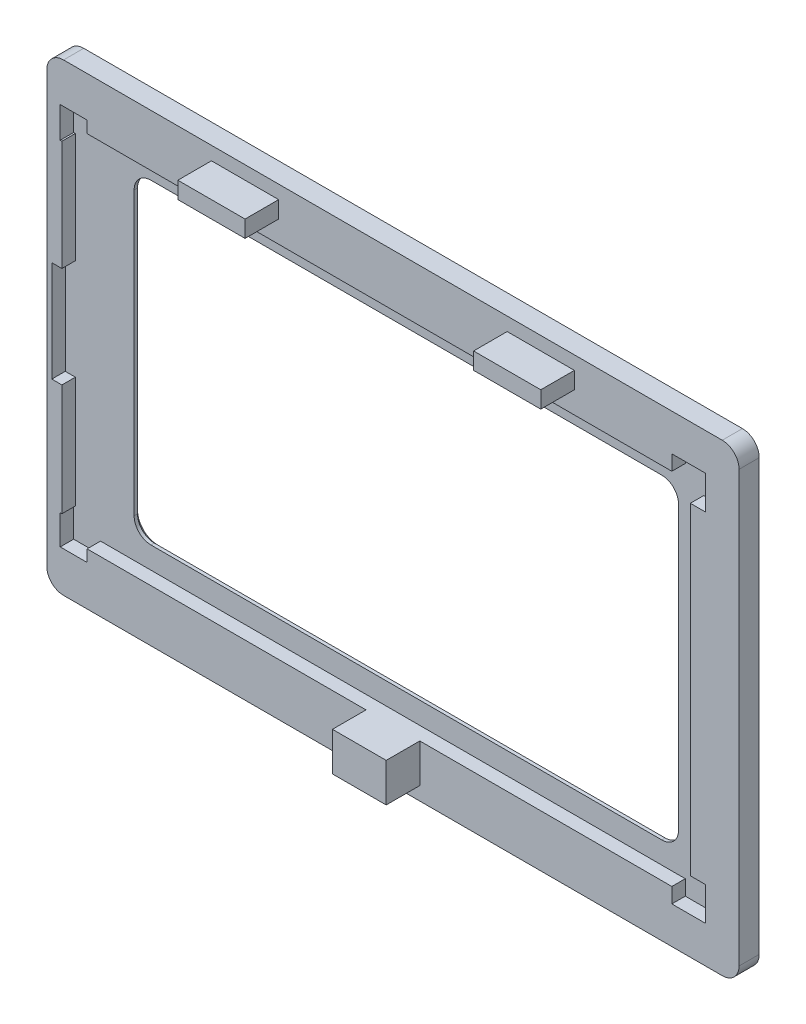
SolidWorks part; units mm, degrees
ref_plane "Front Plane" through (0, 0, 0) normal (0, 0, 1) x (1, 0, 0)
ref_plane "Top Plane" through (0, 0, 0) normal (0, 1, 0) x (1, 0, 0)
ref_plane "Right Plane" through (0, 0, 0) normal (1, 0, 0) x (0, 0, -1)
sketch "Sketch1" plane through (0, 0, 0) normal (0, 0, 1) x (1, 0, 0)
  line L1 (113.8284, 62.9439) -> (10.8284, 62.9439)
  line L2 (113.8284, 62.9439) -> (113.8284, -6.0561)
  line L3 (113.8284, -6.0561) -> (10.8284, -6.0561)
  line L4 (10.8284, 62.9439) -> (10.8284, -6.0561)
  dimension "D1" = 69
  dimension "D2" = 103
extrude "Boss-Extrude1" add sketch "Sketch1" along normal blind 3
sketch "Sketch2" plane through (0, 0, 3) normal (0, 0, 1) x (1, 0, 0)
  line L0 (10.8284, 62.9439) -> (10.8284, -6.0561) construction
  line L1 (21.8284, 51.9439) -> (102.8284, 51.9439)
  line L2 (21.8284, 51.9439) -> (21.8284, 4.9439)
  line L3 (21.8284, 4.9439) -> (102.8284, 4.9439)
  line L4 (102.8284, 51.9439) -> (102.8284, 4.9439)
  line L5 (113.8284, 62.9439) -> (10.8284, 62.9439) construction
  line L6 (113.8284, -6.0561) -> (113.8284, 62.9439) construction
  line L7 (10.8284, -6.0561) -> (113.8284, -6.0561) construction
  dimension "D1" = 11
  dimension "D2" = 11
  dimension "D3" = 11
  dimension "D4" = 11
extrude "Cut-Extrude1" cut sketch "Sketch2" against normal blind 3
sketch "Sketch3" plane through (0, 0, 3) normal (0, 0, 1) x (1, 0, 0)
  line L0 (113.8284, -6.0561) -> (113.8284, 62.9439) construction
  line L1 (13.0784, 55.1939) -> (106.5784, 55.1939)
  line L2 (13.0784, 55.1939) -> (13.0784, 35.9439)
  line L3 (13.0784, 1.6939) -> (106.5784, 1.6939)
  line L11 (106.5784, 55.1939) -> (106.5784, 1.6939)
  line L12 (13.0784, 20.9439) -> (13.0784, 1.6939)
  line L13 (13.0784, 35.9439) -> (11.5784, 35.9439)
  line L15 (13.0784, 20.9439) -> (11.5784, 20.9439)
  line L16 (11.5784, 35.9439) -> (11.5784, 20.9439)
  line L18 (21.8284, 51.9439) -> (21.8284, 4.9439) construction
  point P13 (113.8284, 28.4439)
  point P14 (106.5784, 28.4439)
  dimension "D1" = 93.5
  dimension "D2" = 53.5
  dimension "D3" = 8.75
  dimension "D4" = 1.5
  dimension "D5" = 15
  dimension "D6" = 19.25
extrude "Cut-Extrude2" cut sketch "Sketch3" against normal blind 2
fillet "Fillet2" radius 2.5 4 edges at (113.8284, 62.9439, 1.5) (10.8284, 62.9439, 1.5) (10.8284, -6.0561, 1.5) (113.8284, -6.0561, 1.5)
fillet "Fillet3" radius 2.5 4 edges at (21.8284, 51.9439, 0.5) (21.8284, 4.9439, 0.5) (102.8284, 4.9439, 0.5) (102.8284, 51.9439, 0.5)
chamfer "Chamfer1" distance 0.5 angle 45 8 edges at (62.3284, 4.9439, 0) (102.8284, 28.4439, 0) (62.3284, 51.9439, 0) (21.8284, 28.4439, 0) (102.0961, 51.2116, 0) (102.0961, 5.6761, 0) (22.5606, 51.2116, 0) (22.5606, 5.6761, 0)
sketch "Sketch4" plane through (0, 0, 3) normal (0, 0, 1) x (1, 0, 0)
  line L0 (14.3284, 52.8439) -> (12.8284, 52.8439) construction
  line L1 (16.8284, 55.1939) -> (16.8284, 56.9439)
  line L2 (106.5784, 55.1939) -> (13.0784, 55.1939) construction
  line L4 (16.8284, 55.1939) -> (13.0784, 55.1939)
  line L5 (13.0784, 55.1939) -> (13.0784, 52.3439)
  line L7 (13.0784, 55.1939) -> (13.0784, 35.9439) construction
  line L8 (13.0784, 52.3439) -> (12.8284, 52.3439)
  line L9 (16.8284, 56.9439) -> (12.8284, 56.9439)
  line L10 (12.8284, 56.4439) -> (12.8284, 60.9439) construction
  line L11 (12.8284, 56.9439) -> (12.8284, 52.3439)
  line L12 (16.3284, 56.4439) -> (12.8284, 56.4439) construction
  line L13 (16.3284, 52.8439) -> (16.3284, 56.4439) construction
  line L14 (103.8284, 55.1939) -> (103.8284, 57.4439)
  line L15 (103.8284, 57.4439) -> (108.8284, 57.4439)
  line L16 (108.8284, 57.4439) -> (108.8284, 52.4439)
  line L17 (108.8284, 52.4439) -> (106.5784, 52.4439)
  line L18 (106.5784, 1.6939) -> (106.5784, 55.1939) construction
  line L19 (103.8284, 55.1939) -> (106.5784, 55.1939)
  line L20 (106.5784, 55.1939) -> (106.5784, 52.4439)
  line L21 (104.3284, 56.9439) -> (104.3284, 52.9439) construction
  line L22 (108.3284, 56.9439) -> (104.3284, 56.9439) construction
  line L23 (108.3284, 56.9439) -> (108.3284, 52.9439) construction
  line L24 (108.3284, 52.9439) -> (104.3284, 52.9439) construction
  line L25 (16.8284, 1.6939) -> (16.8284, -0.0561)
  line L26 (13.0784, 1.6939) -> (106.5784, 1.6939) construction
  line L27 (16.8284, -0.0561) -> (12.8284, -0.0561)
  line L28 (12.8284, -4.0561) -> (12.8284, 0.4439) construction
  line L29 (16.8284, 1.6939) -> (13.0784, 1.6939)
  line L30 (13.0784, 1.6939) -> (13.0784, 4.3439)
  line L31 (13.0784, 20.9439) -> (13.0784, 1.6939) construction
  line L32 (13.0784, 4.3439) -> (12.8284, 4.3439)
  line L33 (12.8284, 3.8439) -> (12.8284, 7.3439) construction
  line L34 (12.8284, 4.3439) -> (12.8284, -0.0561)
  line L35 (12.8284, 3.8439) -> (16.3284, 3.8439) construction
  line L36 (16.3284, 3.8439) -> (16.3284, 0.4439) construction
  line L37 (16.3284, 0.4439) -> (12.8284, 0.4439) construction
  line L38 (103.8284, 1.6939) -> (103.8284, -0.5561)
  line L39 (103.8284, -0.5561) -> (108.8284, -0.5561)
  line L40 (108.8284, -0.5561) -> (108.8284, 4.4439)
  line L41 (108.8284, 4.4439) -> (106.5784, 4.4439)
  line L42 (106.5784, 4.4439) -> (106.5784, 1.6939)
  line L43 (106.5784, 1.6939) -> (103.8284, 1.6939)
  line L44 (104.3284, 3.9439) -> (104.3284, -0.0561) construction
  line L45 (108.3284, -0.0561) -> (104.3284, -0.0561) construction
  line L46 (108.3284, 3.9439) -> (108.3284, -0.0561) construction
  line L47 (108.3284, 3.9439) -> (104.3284, 3.9439) construction
  dimension "D1" = 0.5
  dimension "D2" = 0.5
  dimension "D3" = 0.5
  dimension "D4" = 0.5
  dimension "D5" = 0.5
  dimension "D6" = 0.5
  dimension "D7" = 0.5
  dimension "D8" = 0.5
  dimension "D9" = 0.5
  dimension "D10" = 0.5
  dimension "D11" = 0.5
  dimension "D12" = 0.5
  dimension "D13" = 0.5
  dimension "D14" = 0.5
extrude "Cut-Extrude3" cut sketch "Sketch4" against normal up to surface (2 mm away) up to face at (36.0784, 28.4439, 1)
sketch "Sketch5" plane through (0, 0, 3) normal (0, 0, 1) x (1, 0, 0)
  line L0 (12.8284, 60.9439) -> (111.8284, 60.9439) construction
  line L1 (79.3284, 60.9439) -> (89.3284, 60.9439)
  line L2 (79.3284, 60.9439) -> (79.3284, 58.4439)
  line L3 (79.3284, 58.4439) -> (89.3284, 58.4439)
  line L4 (89.3284, 60.9439) -> (89.3284, 58.4439)
  line L5 (12.8284, 56.4439) -> (12.8284, 60.9439) construction
  line L6 (35.3284, 60.9439) -> (45.3284, 60.9439)
  line L7 (35.3284, 60.9439) -> (35.3284, 58.4439)
  line L8 (35.3284, 58.4439) -> (45.3284, 58.4439)
  line L9 (45.3284, 60.9439) -> (45.3284, 58.4439)
  line L10 (111.8284, 60.9439) -> (111.8284, -4.0561) construction
  dimension "D1" = 2.5
  dimension "D2" = 10
  dimension "D3" = 22.5
  dimension "D4" = 22.5
extrude "Boss-Extrude2" add sketch "Sketch5" along normal blind 5
sketch "Sketch6" plane through (0, 0, 3) normal (0, 0, 1) x (1, 0, 0)
  line L5 (111.8284, -4.0561) -> (12.8284, -4.0561) construction
  line L6 (58.3284, -4.0561) -> (66.3284, -4.0561)
  line L7 (58.3284, -4.0561) -> (58.3284, 1.6939)
  line L8 (58.3284, 1.6939) -> (66.3284, 1.6939)
  line L9 (66.3284, -4.0561) -> (66.3284, 1.6939)
  line L10 (16.8284, 1.6939) -> (103.8284, 1.6939) construction
  line L12 (13.3284, -6.0561) -> (111.3284, -6.0561) construction
  point P2 (62.3284, -6.0561)
  point P3 (62.3284, -4.0561)
  point P12 (99.7857, 1.6939)
  dimension "D1" = 8
extrude "Boss-Extrude3" add sketch "Sketch6" along normal blind 5
